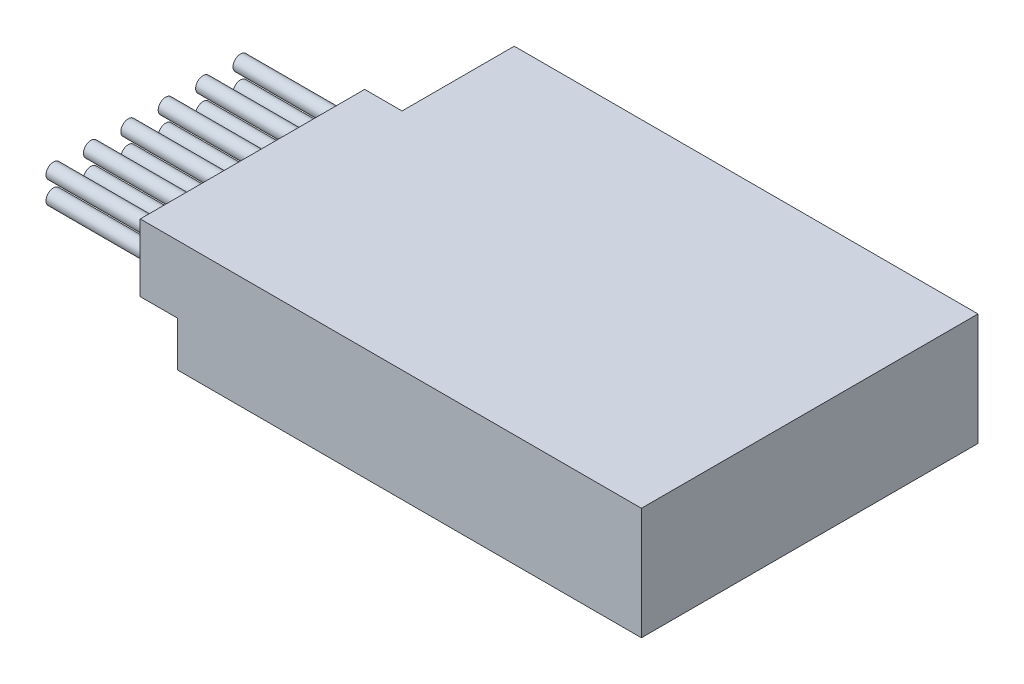
SolidWorks part; units mm, degrees
ref_plane "Front Plane" through (0, 0, 0) normal (0, 0, 1) x (1, 0, 0)
ref_plane "Top Plane" through (0, 0, 0) normal (0, 1, 0) x (1, 0, 0)
ref_plane "Right Plane" through (0, 0, 0) normal (1, 0, 0) x (0, 0, -1)
sketch "Sketch1" plane through (0, 0, 0) normal (0, 1, 0) x (1, 0, 0)
  line L1 (15.5, 11.25) -> (-15.5, 11.25)
  line L2 (15.5, 11.25) -> (15.5, -11.25)
  line L3 (15.5, -11.25) -> (-15.5, -11.25)
  line L4 (-15.5, 11.25) -> (-15.5, -11.25)
  line L5 (15.5, 11.25) -> (-15.5, -11.25) construction
  line L6 (15.5, -11.25) -> (-15.5, 11.25) construction
  point P0 (0, 0)
  dimension "D1" = 22.5
  dimension "D2" = 31
extrude "Boss-Extrude1" add sketch "Sketch1" along normal blind 7.5
sketch "Sketch2" plane through (-15.5, 0, 0) normal (-1, 0, 0) x (0, 0, 1)
  line L1 (11.25, 7.5) -> (-3.75, 7.5)
  line L2 (11.25, 7.5) -> (11.25, 3)
  line L3 (11.25, 3) -> (-3.75, 3)
  line L4 (-3.75, 7.5) -> (-3.75, 3)
  dimension "D1" = 15
  dimension "D2" = 4.5
extrude "Boss-Extrude2" add sketch "Sketch2" along normal blind 2.5
sketch "Sketch3" plane through (-18, 0, 0) normal (-1, 0, 0) x (0, 0, 1)
  line L0 (-3.75, 7.5) -> (-3.75, 3) construction
  line L1 (11.25, 7.5) -> (-3.75, 7.5) construction
  circle A0 centre (-2.45, 6.2) radius 0.5
  circle A1 centre (0.05, 6.2) radius 0.5
  circle A2 centre (2.55, 6.2) radius 0.5
  circle A3 centre (5.05, 6.2) radius 0.5
  circle A4 centre (7.55, 6.2) radius 0.5
  circle A5 centre (10.05, 6.2) radius 0.5
  circle A6 centre (-2.45, 4.7) radius 0.5
  circle A7 centre (0.05, 4.7) radius 0.5
  circle A8 centre (2.55, 4.7) radius 0.5
  circle A9 centre (5.05, 4.7) radius 0.5
  circle A10 centre (7.55, 4.7) radius 0.5
  circle A11 centre (10.05, 4.7) radius 0.5
  dimension "D8" = 1
  dimension "D1" = 2.5
  dimension "D2" = 2.5
  dimension "D3" = 2.5
  dimension "D4" = 2.5
  dimension "D5" = 2.5
  dimension "D6" = 1.3
  dimension "D7" = 1.3
  dimension "D9" = 2
extrude "Boss-Extrude3" add sketch "Sketch3" along normal blind 7
